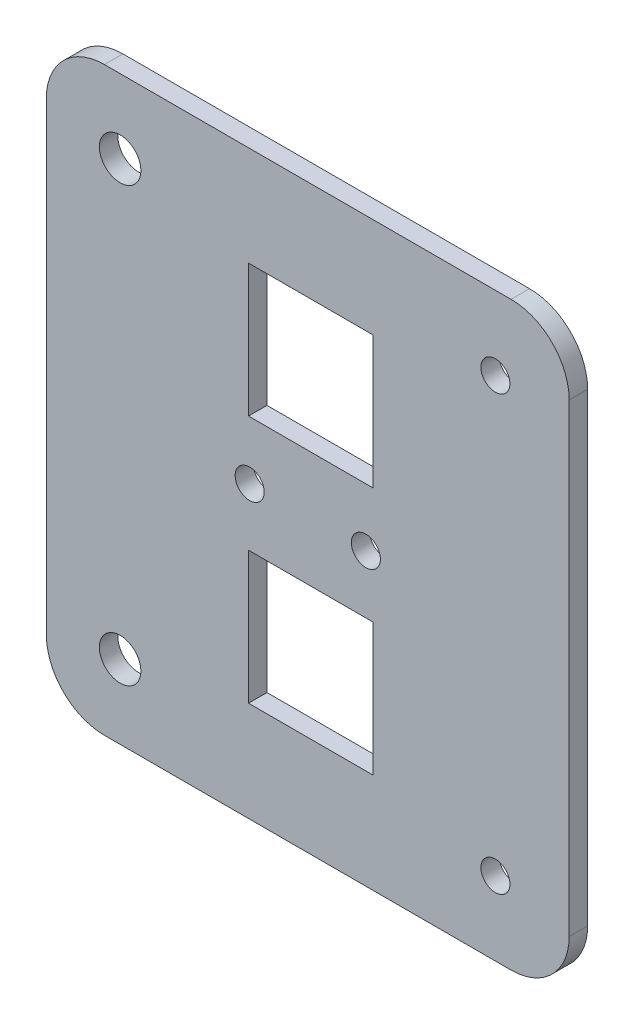
SolidWorks part; units mm, degrees
ref_plane "Front Plane" through (0, 0, 0) normal (0, 0, 1) x (1, 0, 0)
ref_plane "Top Plane" through (0, 0, 0) normal (0, 1, 0) x (1, 0, 0)
ref_plane "Right Plane" through (0, 0, 0) normal (1, 0, 0) x (0, 0, -1)
sketch "Sketch1" plane through (0, 0, 0) normal (0, 0, 1) x (1, 0, 0)
  line L0 (35, 45) -> (-35, 45) construction
  line L1 (-45, -55) -> (45, -55)
  line L2 (-45, -55) -> (-45, 45)
  line L3 (-45, 45) -> (45, 45)
  line L4 (45, -55) -> (45, 45)
  line L5 (-43.1231, -55) -> (43.1231, -55) construction
  line L6 (-45, 35) -> (-45, 25) construction
  line L7 (45, 25) -> (45, 35) construction
  circle A1 centre (32.3, -42.3) radius 2.5 construction
  circle A2 centre (-32.3, -42.3) radius 3.57 construction
  circle A5 centre (32.3, -42.3) radius 2.5
  circle A6 centre (-32.3, -42.3) radius 3.57
  circle A8 centre (-32.3, 32.3) radius 3.57 construction
  circle A9 centre (-32.3, 32.3) radius 3.57
  circle A10 centre (32.3, 32.3) radius 2.5 construction
  circle A11 centre (32.3, 32.3) radius 2.5
extrude "Boss-Extrude1" add sketch "Sketch1" against normal blind 3.18 from offset 19.16
fillet "Fillet1" radius 10 4 edges at (45, -55, 17.57) (-45, -55, 17.57) (-45, 45, 17.57) (45, 45, 17.57)
sketch "Sketch2" plane through (0, 0, 19.16) normal (0, 0, 1) x (1, 0, 0)
  line L0 (0, 45) -> (0, -55) construction
  line L1 (35, 45) -> (-35, 45) construction
  line L2 (-35, -55) -> (35, -55) construction
  line L3 (-10, -5) -> (10, -5) construction
  circle A0 centre (10, -5) radius 2.5
  circle A1 centre (-10, -5) radius 2.5
  point P9 (0, -5)
  dimension "D2" = 5
  dimension "D1" = 20
extrude "Cut-Extrude1" cut sketch "Sketch2" against normal blind 10
ref_plane "Midplane" through (0, -5, 0) normal (0, 1, 0) x (1, 0, 0)
sketch "Sketch3" plane through (0, 0, 15.98) normal (0, 0, -1) x (-1, 0, 0)
  line L0 (-45, -45) -> (-45, 35) construction
  line L1 (-10, -5) -> (-10, -15) construction
  line L2 (0, 0) -> (0, -15) construction
  line L3 (-10, -5) -> (10, -5) construction
  line L4 (10.2, 27.8105) -> (-11.2, 27.8105)
  line L5 (10.2, -15) -> (-11.2, -15)
  line L6 (10.2, -15) -> (10.2, -37.8105)
  line L7 (10.2, -37.8105) -> (-11.2, -37.8105)
  line L8 (-11.2, -15) -> (-11.2, -37.8105)
  line L9 (10.2, 5) -> (10.2, 27.8105)
  line L10 (-11.2, 5) -> (-11.2, 27.8105)
  line L11 (10.2, 5) -> (-11.2, 5)
  dimension "D1" = 10
  dimension "D2" = 21.4
  dimension "D3" = 33.8
extrude "Cut-Extrude2" cut sketch "Sketch3" against normal through all
sketch "Sketch4" plane through (0, 0, 19.16) normal (0, 0, 1) x (1, 0, 0)
  circle A0 centre (-30.5474, -25.8964) radius 2.5
  circle A1 centre (35.4512, -25.8964) radius 2.5
  dimension "D1" = 5
  dimension "D2" = 5
sketch "Sketch5" plane through (0, 27.8105, 0) normal (0, -1, 0) x (1, 0, 0)
  line L0 (-10.2, 15.98) -> (-10.2, 5.6496)
  line L1 (-10.2, 5.6496) -> (11.2, 5.6496)
  line L2 (11.2, 5.6496) -> (11.2, 15.98)
  line L3 (-10.2, 15.98) -> (11.2, 15.98)
